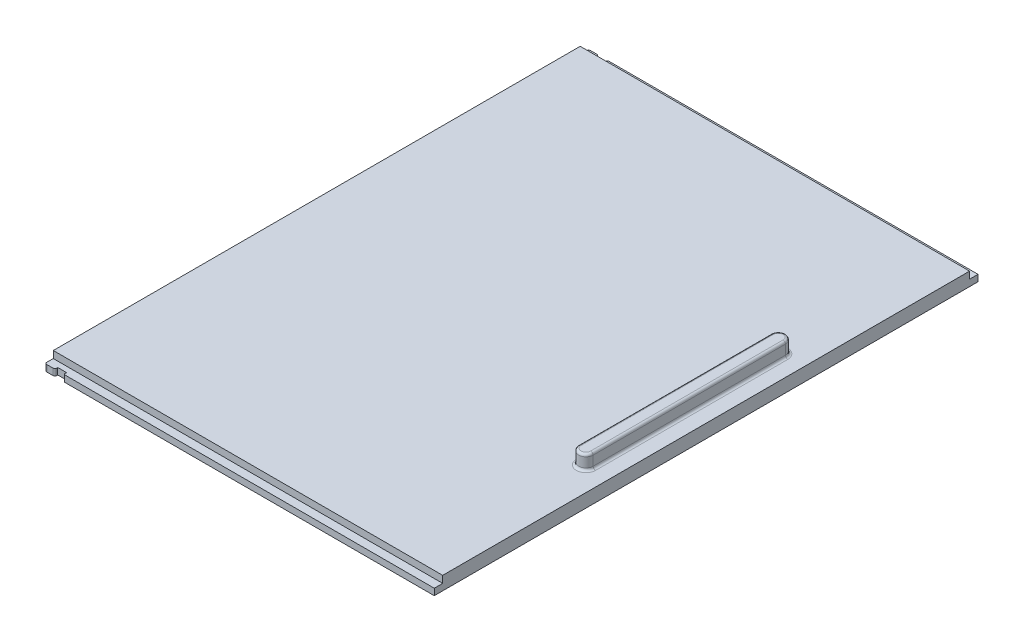
SolidWorks part; units mm, degrees
ref_plane "Front Plane" through (0, 0, 0) normal (0, 0, 1) x (1, 0, 0)
ref_plane "Top Plane" through (0, 0, 0) normal (0, 1, 0) x (1, 0, 0)
ref_plane "Right Plane" through (0, 0, 0) normal (1, 0, 0) x (0, 0, -1)
sketch "Sketch1" plane through (0, 0, 0) normal (0, 1, 0) x (1, 0, 0)
  line L1 (0, 0) -> (81, 0)
  line L2 (0, 0) -> (0, 116)
  line L3 (0, 116) -> (81, 116)
  line L4 (81, 0) -> (81, 116)
  dimension "D1" = 116
  dimension "D2" = 81
extrude "Boss-Extrude1" add sketch "Sketch1" along normal blind 3
sketch "Sketch2" plane through (81, 0, 0) normal (1, 0, 0) x (0, 0, -1)
  line L0 (0, 0) -> (116, 0) construction
  line L1 (0, 3) -> (3, 3)
  line L2 (0, 3) -> (0, 0)
  line L3 (0, 0) -> (1.25, 0)
  line L4 (3, 3) -> (3, 1.75)
  line L5 (3, 1.75) -> (1.25, 1.75)
  line L6 (1.25, 1.75) -> (1.25, 0)
  line L7 (114.75, 0) -> (116, 0)
  line L11 (58, 3) -> (58, 0) construction
  line L12 (0, 3) -> (116, 3) construction
  line L22 (116, 3) -> (113, 3)
  line L25 (114.75, 1.75) -> (113, 1.75)
  line L26 (113, 1.75) -> (113, 3)
  line L31 (114.75, 1.75) -> (114.75, 0)
  line L35 (116, 3) -> (116, 0)
  dimension "D1" = 3
  dimension "D2" = 1.25
  dimension "D3" = 1.25
  dimension "D4" = 3
extrude "Cut-Extrude2" cut sketch "Sketch2" against normal up to surface (81 mm away) up to face at (0, 1.5, -58)
sketch "Sketch4" plane through (81, 0, 0) normal (1, 0, 0) x (0, 0, -1)
  line L17 (58, 3) -> (58, 0) construction
  line L18 (3, 3) -> (113, 3) construction
  line L19 (1.25, 0) -> (114.75, 0) construction
  line L36 (3.2, 3) -> (3, 3)
  line L37 (3, 3) -> (3, 1.75)
  line L38 (3, 1.75) -> (3, 3) construction
  line L39 (1.45, 0) -> (1.45, 1.55)
  line L40 (1.45, 1.55) -> (3.2, 1.55)
  line L41 (3.2, 1.55) -> (3.2, 3)
  line L42 (1.45, 0) -> (1.45, 1.55)
  line L43 (1.45, 1.55) -> (3.2, 1.55)
  line L44 (3.2, 1.55) -> (3.2, 3)
  line L45 (3, 1.75) -> (1.25, 1.75)
  line L46 (1.25, 1.75) -> (1.25, 0)
  line L47 (1.25, 0) -> (1.45, 0)
  line L48 (114.75, 0) -> (114.55, 0)
  line L49 (114.75, 1.75) -> (114.75, 0)
  line L50 (113, 1.75) -> (114.75, 1.75)
  line L51 (112.8, 1.55) -> (112.8, 3)
  line L52 (114.55, 1.55) -> (112.8, 1.55)
  line L53 (114.55, 0) -> (114.55, 1.55)
  line L54 (113, 3) -> (113, 1.75)
  line L55 (112.8, 3) -> (113, 3)
  dimension "D1" = 0.2
extrude "Cut-Extrude3" cut sketch "Sketch4" against normal up to surface (81 mm away) up to face at (0, 1.625, -58)
sketch "Sketch6" plane through (0, 0, -1.45) normal (0, 0, 1) x (1, 0, 0)
  line L0 (3, 0.775) -> (0, 0.775) construction
  line L1 (0, 1.55) -> (0, 0) construction
  line L3 (2.075, 0) -> (3.925, 0)
  line L4 (2.075, 0) -> (2.075, 1.55)
  line L5 (2.075, 1.55) -> (3.925, 1.55)
  line L6 (3.925, 0) -> (3.925, 1.55)
  line L7 (2.075, 0) -> (3.925, 1.55) construction
  line L8 (2.075, 1.55) -> (3.925, 0) construction
  line L9 (0, 1.55) -> (81, 1.55) construction
  line L10 (0, 1.55) -> (81, 1.55) construction
  dimension "D1" = 3
  dimension "D3" = 1.85
  dimension "D4" = 0.775
extrude "Cut-Extrude5" cut sketch "Sketch6" against normal blind 0.6
fillet "Fillet6" radius 0.4 1 edges at (2.075, 0.775, -1.45)
chamfer "Chamfer2" distance 0.2 angle 45 1 edges at (3.925, 0.775, -1.45)
sketch "Sketch7" plane through (0, 0, -114.55) normal (0, 0, -1) x (-1, 0, 0)
  line L0 (-3, 0.775) -> (0, 0.775) construction
  line L3 (-2.075, 1.55) -> (-3.925, 1.55)
  line L4 (-2.075, 1.55) -> (-2.075, 0)
  line L5 (-2.075, 0) -> (-3.925, 0)
  line L6 (-3.925, 1.55) -> (-3.925, 0)
  line L7 (-2.075, 1.55) -> (-3.925, 0) construction
  line L8 (-2.075, 0) -> (-3.925, 1.55) construction
  line L9 (0, 0) -> (0, 1.55) construction
  line L10 (0, 1.55) -> (-81, 1.55) construction
  dimension "D1" = 3
  dimension "D3" = 1.85
  dimension "D4" = 0.775
extrude "Cut-Extrude6" cut sketch "Sketch7" against normal blind 0.6
fillet "Fillet7" radius 0.4 1 edges at (2.075, 0.775, -114.55)
chamfer "Chamfer3" distance 0.2 angle 45 1 edges at (3.925, 0.775, -114.55)
sketch "Sketch9" plane through (0, 3, 0) normal (0, 1, 0) x (1, 0, 0)
  line L0 (76, 38) -> (76, 78) construction
  line L1 (74.5, 38) -> (74.5, 78)
  line L2 (77.5, 38) -> (77.5, 78)
  line L3 (76, 78) -> (76, 112.8) construction
  line L5 (0, 112.8) -> (81, 112.8) construction
  line L14 (76, 38) -> (76, 3.2) construction
  line L15 (0, 3.2) -> (81, 3.2) construction
  line L16 (81, 3.2) -> (81, 112.8) construction
  arc A0 (74.5, 38) -> (77.5, 38) centre (76, 38) ccw
  arc A1 (77.5, 78) -> (74.5, 78) centre (76, 78) ccw
  point P2 (76, 58)
  dimension "D1" = 3
  dimension "D2" = 40
  dimension "D3" = 5
sketch "Sketch10" plane through (0, 0, 0) normal (0, -1, 0) x (-1, 0, 0)
  line L1 (0, 1.45) -> (-81, 1.45)
  line L2 (0, 1.45) -> (0, 114.55)
  line L3 (0, 114.55) -> (-81, 114.55)
  line L4 (-81, 1.45) -> (-81, 114.55)
extrude "Cut-Extrude7" cut sketch "Sketch10" against normal blind 0.2
fillet "Fillet8" radius 0.4 2 edges at (0, 0.875, -114.55) (0, 0.875, -1.45)
extrude "Boss-Extrude2" add sketch "Sketch9" along normal blind 3
fillet "Fillet10" radius 0.5 8 edges at (74.5, 3, -58) (76, 3, -79.5) (77.5, 3, -58) (74.5, 6, -58) (76, 6, -79.5) (77.5, 6, -58) (76, 6, -36.5) (76, 3, -36.5)
